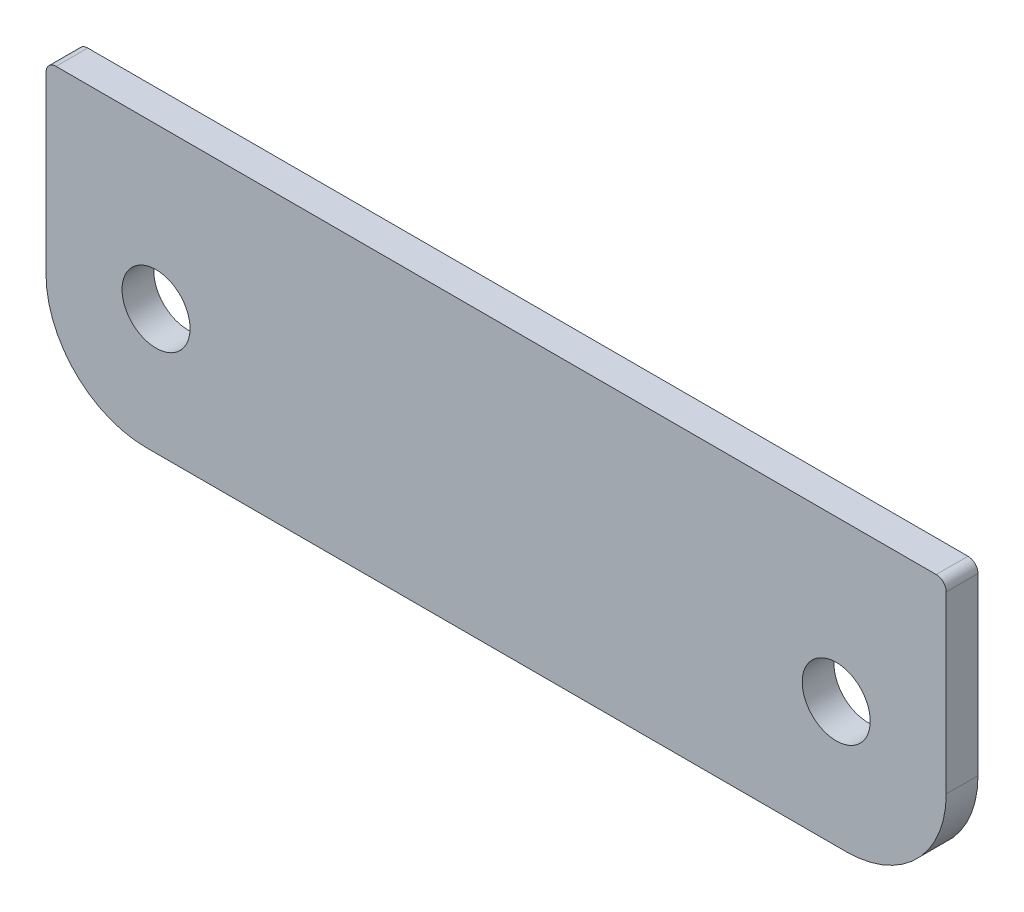
SolidWorks part; units mm, degrees
ref_plane "Front Plane" through (0, 0, 0) normal (0, 0, 1) x (1, 0, 0)
ref_plane "Top Plane" through (0, 0, 0) normal (0, 1, 0) x (1, 0, 0)
ref_plane "Right Plane" through (0, 0, 0) normal (1, 0, 0) x (0, 0, -1)
sketch "Sketch1" plane through (0, 0, 0) normal (0, 0, 1) x (1, 0, 0)
  line L0 (-34, 0) -> (34, 0) construction
  line L3 (-45, 12.5) -> (-45, 16)
  line L5 (-45, 12.5) -> (-45, -12.5)
  line L6 (-45, -12.5) -> (45, -12.5)
  line L7 (45, 12.5) -> (45, -12.5)
  line L8 (0, -12.5) -> (0, 12.5) construction
  line L9 (-45, 0) -> (45, 0) construction
  line L11 (-45, 16) -> (45, 16)
  line L12 (45, 16) -> (45, 12.5)
  circle A2 centre (34, 0) radius 3.4
  circle A3 centre (-34, 0) radius 3.4
  point P0 (0, 0)
  point P1 (0, 0)
  dimension "D2" = 90
  dimension "D3" = 6.8
  dimension "D4" = 25
  dimension "D1" = 68
  dimension "D5" = 3.5
extrude "Boss-Extrude1" add sketch "Sketch1" along normal mid plane 3.175
fillet "Fillet1" radius 10 2 edges at (45, -12.5, 0) (-45, -12.5, 0)
fillet "Fillet2" radius 1 2 edges at (-45, 16, 0) (45, 16, 0)
